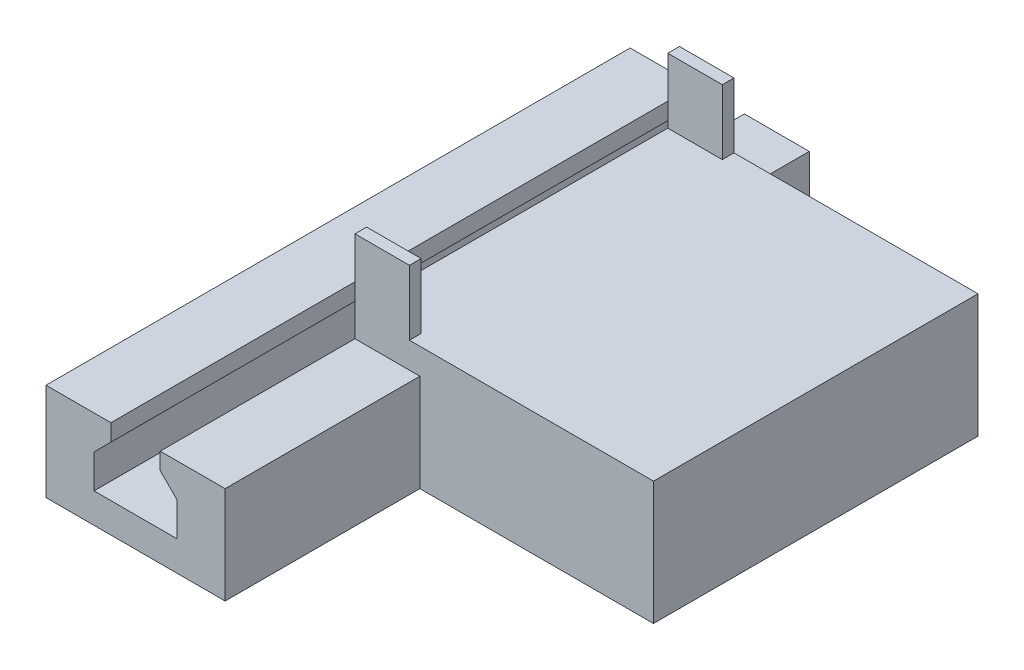
SolidWorks part; units mm, degrees
ref_plane "Plan de face" through (0, 0, 0) normal (0, 0, 1) x (1, 0, 0)
ref_plane "Plan de dessus" through (0, 0, 0) normal (0, 1, 0) x (1, 0, 0)
ref_plane "Plan de droite" through (0, 0, 0) normal (1, 0, 0) x (0, 0, -1)
sketch "Esquisse1" plane through (0, 0, 0) normal (0, 0, 1) x (1, 0, 0)
  line L0 (0, 0) -> (0, -5.2499) construction
  line L5 (0, 0) -> (0, 6.7252) construction
  line L6 (0, 0) -> (7.76, 0) construction
  line L7 (0, 0) -> (-6.4576, 0) construction
  line L8 (-3.2, 0) -> (3.2, 0)
  line L9 (-3.2, 0) -> (-3.2, 2.6)
  line L10 (3.2, 0) -> (3.2, 2.6)
  line L12 (-1.9, 5.2) -> (-1.9, 3.9)
  line L13 (1.9, 5.2) -> (1.9, 3.9)
  line L14 (-3.2, 2.6) -> (-1.9, 3.9)
  line L15 (1.9, 3.9) -> (3.2, 2.6)
  line L16 (-1.9, 5.2) -> (-6.9, 5.2)
  line L17 (-6.9, 5.2) -> (-6.9, -2.3)
  line L18 (-6.9, -2.3) -> (6.9, -2.3)
  line L19 (6.9, -2.3) -> (6.9, 5.2)
  line L20 (6.9, 5.2) -> (1.9, 5.2)
  point P10 (0, 0)
  point P15 (0, 5.2)
  dimension "D1" = 6.4
  dimension "D2" = 2.6
  dimension "D3" = 2.6
  dimension "D4" = 3.8
  dimension "D5" = 1.3
  dimension "D6" = 1.3
  dimension "D7" = 1.3
  dimension "D8" = 5
  dimension "D9" = 5
  dimension "D10" = 7.5
extrude "Boss.-Extru.1" add sketch "Esquisse1" along normal blind 45
sketch "Esquisse6" plane through (6.9, 0, 0) normal (1, 0, 0) x (0, 0, -1)
  line L0 (-45, -2.3) -> (0, -2.3) construction
  line L1 (-30, -2.3) -> (-5, -2.3)
  line L2 (-30, -2.3) -> (-30, 5.2)
  line L3 (-30, 5.2) -> (-5, 5.2)
  line L4 (-5, -2.3) -> (-5, 5.2)
  line L5 (-45, 5.2) -> (0, 5.2) construction
  line L6 (0, -2.3) -> (0, 5.2) construction
  dimension "D1" = 5
  dimension "D2" = 25
extrude "Boss.-Extru.6" add sketch "Esquisse6" along normal blind 18
sketch "Esquisse7" plane through (0, 5.2, 0) normal (0, 1, 0) x (1, 0, 0)
  line L0 (1.9, -45) -> (1.9, 0) construction
  line L1 (24.9, -30) -> (1.9, -30)
  line L2 (24.9, -30) -> (24.9, -5)
  line L3 (24.9, -5) -> (1.9, -5)
  line L4 (1.9, -30) -> (1.9, -5)
  dimension "D1" = 25
extrude "Boss.-Extru.7" add sketch "Esquisse7" along normal blind 2
sketch "Esquisse8" plane through (0, 7.2, 0) normal (0, 1, 0) x (1, 0, 0)
  line L1 (1.9, -30) -> (6.1, -30)
  line L2 (1.9, -30) -> (1.9, -29.1)
  line L3 (1.9, -29.1) -> (6.1, -29.1)
  line L4 (6.1, -30) -> (6.1, -29.1)
  line L5 (1.9, -5) -> (6.1, -5)
  line L6 (1.9, -5) -> (1.9, -5.9)
  line L7 (1.9, -5.9) -> (6.1, -5.9)
  line L8 (6.1, -5) -> (6.1, -5.9)
  dimension "D1" = 4.2
  dimension "D2" = 4.2
  dimension "D3" = 0.9
  dimension "D4" = 0.9
extrude "Boss.-Extru.8" add sketch "Esquisse8" along normal blind 5
